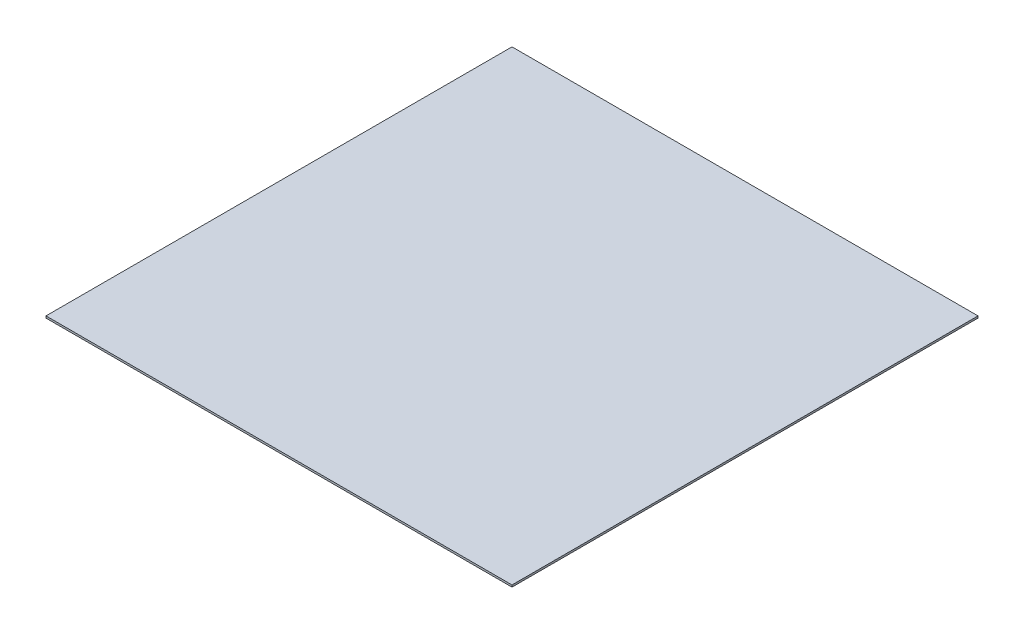
SolidWorks part; units mm, degrees
ref_plane "Front Plane" through (0, 0, 0) normal (0, 0, 1) x (1, 0, 0)
ref_plane "Top Plane" through (0, 0, 0) normal (0, 1, 0) x (1, 0, 0)
ref_plane "Right Plane" through (0, 0, 0) normal (1, 0, 0) x (0, 0, -1)
sketch "Sketch1" plane through (0, 0, 0) normal (0, 1, 0) x (1, 0, 0)
  line L1 (-1524, 1524) -> (1524, 1524)
  line L2 (-1524, 1524) -> (-1524, -1524)
  line L3 (-1524, -1524) -> (1524, -1524)
  line L4 (1524, 1524) -> (1524, -1524)
  line L5 (-1524, 1524) -> (1524, -1524) construction
  line L6 (-1524, -1524) -> (1524, 1524) construction
  point P0 (0, 0)
extrude "Boss-Extrude1" add sketch "Sketch1" along normal blind 12.7
